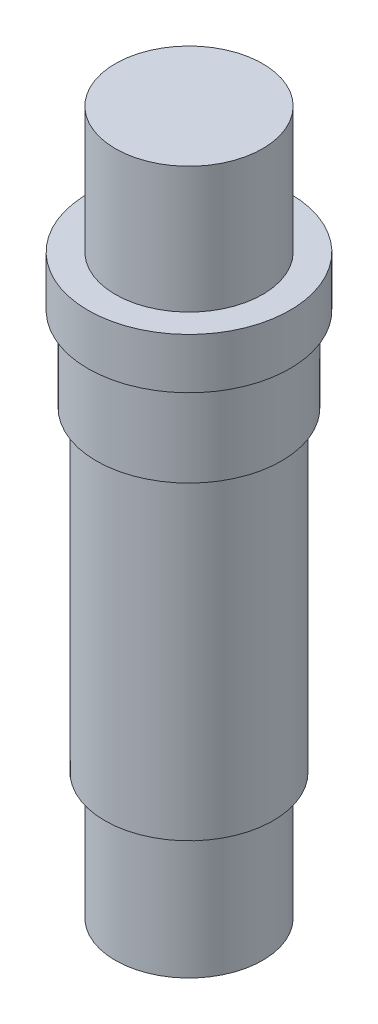
SolidWorks part; units mm, degrees
ref_plane "前视基准面" through (0, 0, 0) normal (0, 0, 1) x (1, 0, 0)
ref_plane "上视基准面" through (0, 0, 0) normal (0, 1, 0) x (1, 0, 0)
ref_plane "右视基准面" through (0, 0, 0) normal (1, 0, 0) x (0, 0, -1)
sketch "草图1" plane through (0, 0, 0) normal (0, 1, 0) x (1, 0, 0)
  circle A0 centre (0, 0) radius 17.5
extrude "凸台-拉伸1" add sketch "草图1" along normal blind 30
sketch "草图2" plane through (0, 30, 0) normal (0, 1, 0) x (1, 0, 0)
  circle A0 centre (0, 0) radius 20
extrude "凸台-拉伸2" add sketch "草图2" along normal blind 75
sketch "草图3" plane through (0, 105, 0) normal (0, 1, 0) x (1, 0, 0)
  circle A0 centre (0, 0) radius 22
extrude "凸台-拉伸3" add sketch "草图3" along normal blind 20
sketch "草图5" plane through (0, 125, 0) normal (0, 1, 0) x (1, 0, 0)
  circle A0 centre (0, 0) radius 24
extrude "凸台-拉伸4" add sketch "草图5" along normal blind 12
sketch "草图6" plane through (0, 137, 0) normal (0, 1, 0) x (1, 0, 0)
  circle A0 centre (0, 0) radius 17.5
extrude "凸台-拉伸5" add sketch "草图6" along normal blind 30
